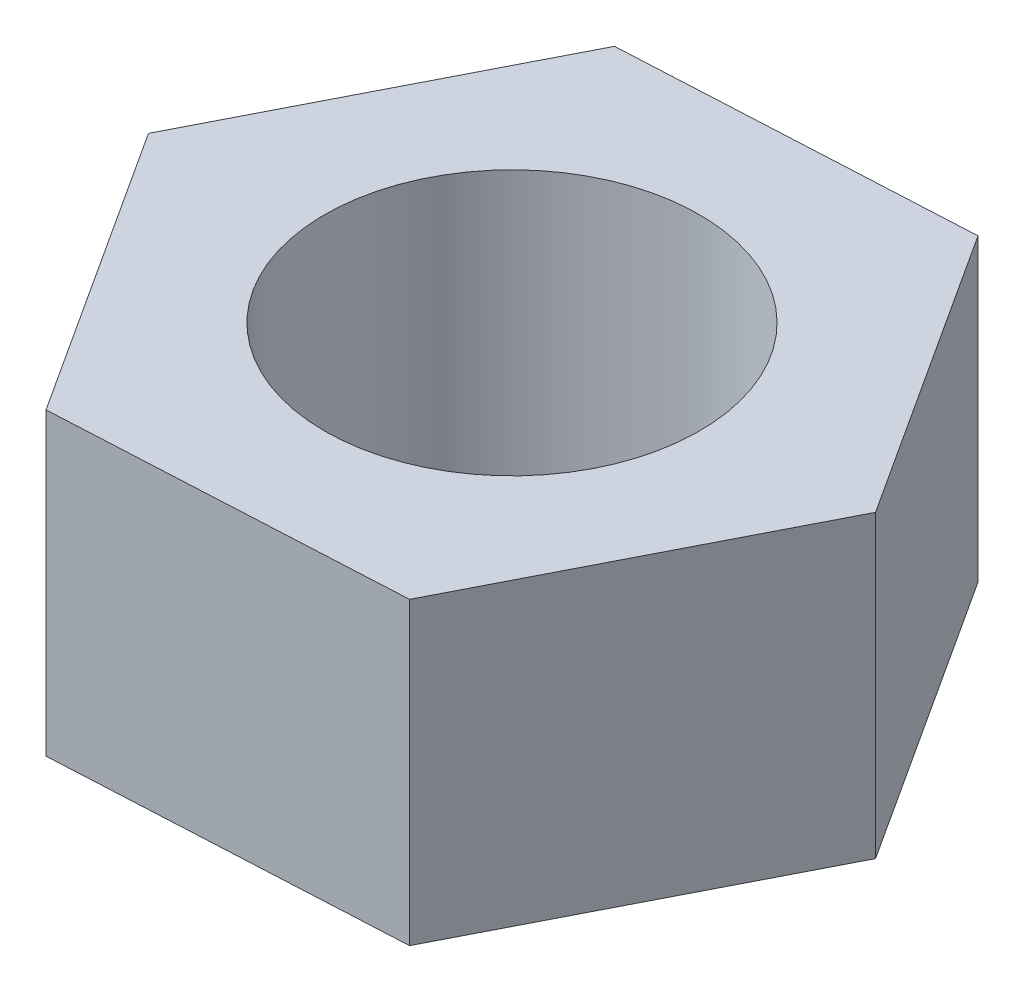
SolidWorks part; units mm, degrees
material "Plain Carbon Steel"
ref_plane "Front Plane" through (0, 0, 0) normal (0, 0, 1) x (1, 0, 0)
ref_plane "Top Plane" through (0, 0, 0) normal (0, 1, 0) x (1, 0, 0)
ref_plane "Right Plane" through (0, 0, 0) normal (1, 0, 0) x (0, 0, -1)
sketch "Sketch1" plane through (0, 0, 0) normal (0, 1, 0) x (1, 0, 0)
  line L1 (6.3766, -9.8475) -> (11.7165, 0.5986)
  line L2 (11.7165, 0.5986) -> (5.3398, 10.4461)
  line L3 (5.3398, 10.4461) -> (-6.3766, 9.8475)
  line L4 (-6.3766, 9.8475) -> (-11.7165, -0.5986)
  line L5 (-11.7165, -0.5986) -> (-5.3398, -10.4461)
  line L6 (-5.3398, -10.4461) -> (6.3766, -9.8475)
  circle A0 centre (0, 0) radius 6.35
  circle A1 centre (0, 0) radius 10.16 construction
  dimension "D1" = 12.7
  dimension "D2" = 3.81
  dimension "D3" = 5.3398
extrude "Boss-Extrude1" add sketch "Sketch1" along normal blind 10.16
